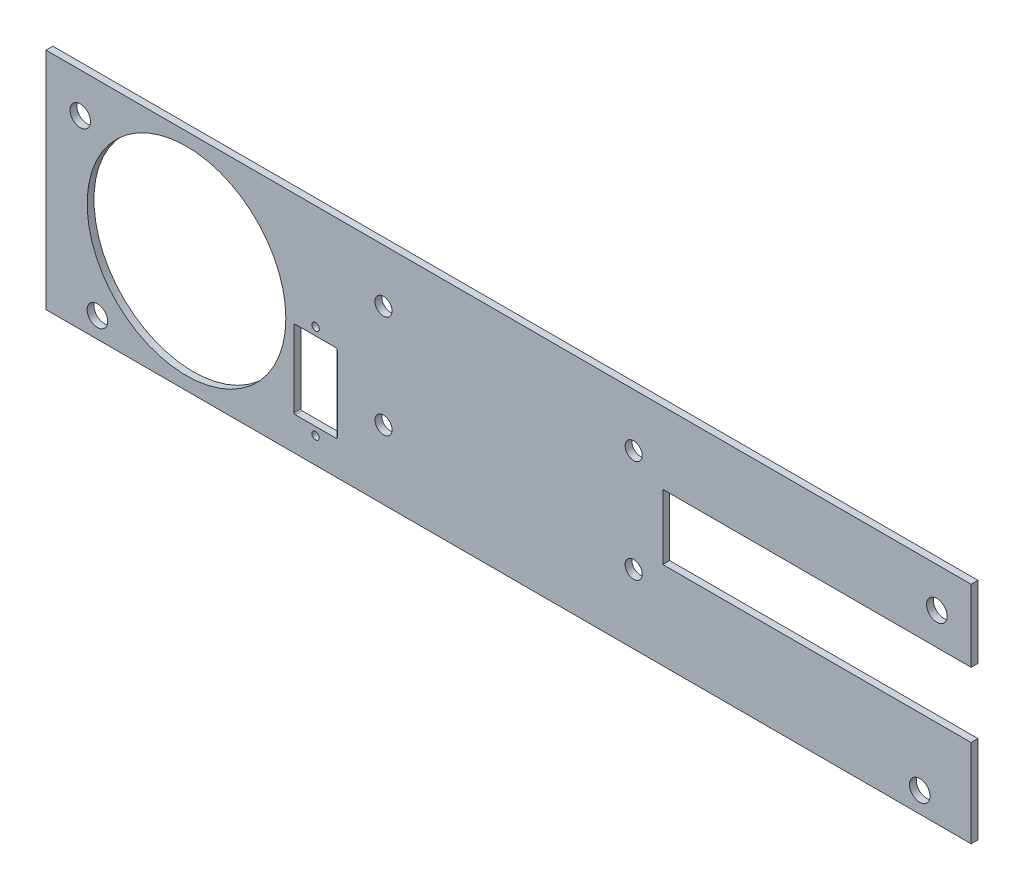
SolidWorks part; units mm, degrees
material "AISI 1020"
ref_plane "Front Plane" through (0, 0, 0) normal (0, 0, 1) x (1, 0, 0)
ref_plane "Top Plane" through (0, 0, 0) normal (0, 1, 0) x (1, 0, 0)
ref_plane "Right Plane" through (0, 0, 0) normal (1, 0, 0) x (0, 0, -1)
sketch "Sketch1" plane through (0, 0, 0) normal (0, 0, 1) x (1, 0, 0)
  line L1 (-135, 30) -> (135, 30)
  line L2 (-135, 30) -> (-135, -30)
  line L3 (-135, -30) -> (135, -30)
  line L4 (135, 30) -> (135, -30)
  line L5 (-135, 30) -> (135, -30) construction
  line L6 (-135, -30) -> (135, 30) construction
  point P0 (0, 0)
  dimension "D1" = 60
  dimension "D2" = 270
extrude "Boss-Extrude1" add sketch "Sketch1" along normal blind 2
sketch "Sketch6" plane through (0, 0, 2) normal (0, 0, 1) x (1, 0, 0)
  line L0 (135, 30) -> (-135, 30) construction
  line L1 (-135, 30) -> (135, 30)
  line L2 (-135, 30) -> (-135, 35.6)
  line L3 (-135, 35.6) -> (135, 35.6)
  line L4 (135, 30) -> (135, 35.6)
  line L5 (-135, 30) -> (-135, -30) construction
  dimension "D1" = 270
  dimension "D2" = 5.6
extrude "Boss-Extrude2" add sketch "Sketch6" against normal blind 2
sketch "Sketch7" plane through (0, 0, 0) normal (0, 0, -1) x (-1, 0, 0)
  circle A0 centre (-36.5, 20.1247) radius 2.5 construction
  circle A1 centre (-36.5, -9.8753) radius 2.5 construction
  circle A2 centre (36.5, -9.8753) radius 2.5 construction
  circle A3 centre (36.5, 20.1247) radius 2.5 construction
  circle A4 centre (125, 24) radius 3 construction
  circle A5 centre (120, -24) radius 3 construction
  circle A6 centre (-125, 24) radius 3 construction
  circle A7 centre (-120, -24) radius 3 construction
  circle A8 centre (-36.5, 20.1247) radius 2.5
  circle A9 centre (-36.5, -9.8753) radius 2.5
  circle A10 centre (36.5, -9.8753) radius 2.5
  circle A11 centre (36.5, 20.1247) radius 2.5
  circle A12 centre (125, 24) radius 3
  circle A13 centre (120, -24) radius 3
  circle A14 centre (-125, 24) radius 3
  circle A15 centre (-120, -24) radius 3
extrude "Cut-Extrude1" cut sketch "Sketch7" against normal through all
sketch "Sketch8" plane through (0, 0, 0) normal (0, 0, -1) x (-1, 0, 0)
  line L2 (-135, -30) -> (-135, 35.6) construction
  line L4 (-135, 4.6) -> (-45, 4.6)
  line L5 (-135, 4.6) -> (-135, 14.6)
  line L6 (-135, 14.6) -> (-45, 14.6)
  line L7 (-45, 4.6) -> (-45, 14.6)
  line L8 (-45, -15.7706) -> (-45, 34.2294) construction
  line L9 (-135, 35.6) -> (135, 35.6) construction
  dimension "D1" = 10
  dimension "D2" = 21
extrude "Cut-Extrude2" cut sketch "Sketch8" against normal through all
sketch "Sketch9" plane through (0, 0, 2) normal (0, 0, 1) x (1, 0, 0)
  line L1 (-135, 35.6) -> (-135, -30) construction
  circle A0 centre (-94, 2.8) radius 29
  point P4 (-135, 2.8)
  dimension "D1" = 58
  dimension "D2" = 41
extrude "Cut-Extrude3" cut sketch "Sketch9" against normal blind 10
sketch "Sketch10" plane through (0, 0, 0) normal (0, 0, -1) x (-1, 0, 0)
  line L0 (62.6238, -19.793) -> (62.6238, 2.305) construction
  line L1 (50.381, -20.174) -> (62.2428, -20.174) construction
  line L2 (50, 2.305) -> (50, -19.793) construction
  line L3 (62.2428, 2.686) -> (50.381, 2.686) construction
  line L4 (62.6238, -19.793) -> (62.6238, 2.305)
  line L5 (50.381, -20.174) -> (62.2428, -20.174)
  line L6 (50, 2.305) -> (50, -19.793)
  line L7 (62.2428, 2.686) -> (50.381, 2.686)
  arc A0 (62.6238, 2.305) -> (62.2428, 2.686) centre (62.2428, 2.305) ccw construction
  arc A1 (62.2428, -20.174) -> (62.6238, -19.793) centre (62.2428, -19.793) ccw construction
  arc A2 (50, -19.793) -> (50.381, -20.174) centre (50.381, -19.793) ccw construction
  arc A3 (50.381, 2.686) -> (50, 2.305) centre (50.381, 2.305) ccw construction
  arc A4 (62.6238, 2.305) -> (62.2428, 2.686) centre (62.2428, 2.305) ccw
  arc A5 (62.2428, -20.174) -> (62.6238, -19.793) centre (62.2428, -19.793) ccw
  arc A6 (50, -19.793) -> (50.381, -20.174) centre (50.381, -19.793) ccw
  arc A7 (50.381, 2.686) -> (50, 2.305) centre (50.381, 2.305) ccw
  circle A8 centre (56.3119, -22.5108) radius 1.0668 construction
  circle A9 centre (56.3119, 5.0228) radius 1.0668 construction
  circle A10 centre (56.3119, -22.5108) radius 1.0668
  circle A11 centre (56.3119, 5.0228) radius 1.0668
extrude "Cut-Extrude4" cut sketch "Sketch10" against normal blind 10
sketch "Sketch11" plane through (0, 0, 2) normal (0, 0, 1) x (1, 0, 0)
  line L0 (45, 4.6) -> (45, 14.6) construction
  line L1 (135, 4.6) -> (45, 4.6)
  line L2 (135, 4.6) -> (135, -4.4)
  line L3 (135, -4.4) -> (45, -4.4)
  line L4 (45, 4.6) -> (45, -4.4)
  dimension "D1" = 9
extrude "Cut-Extrude5" cut sketch "Sketch11" against normal blind 10
